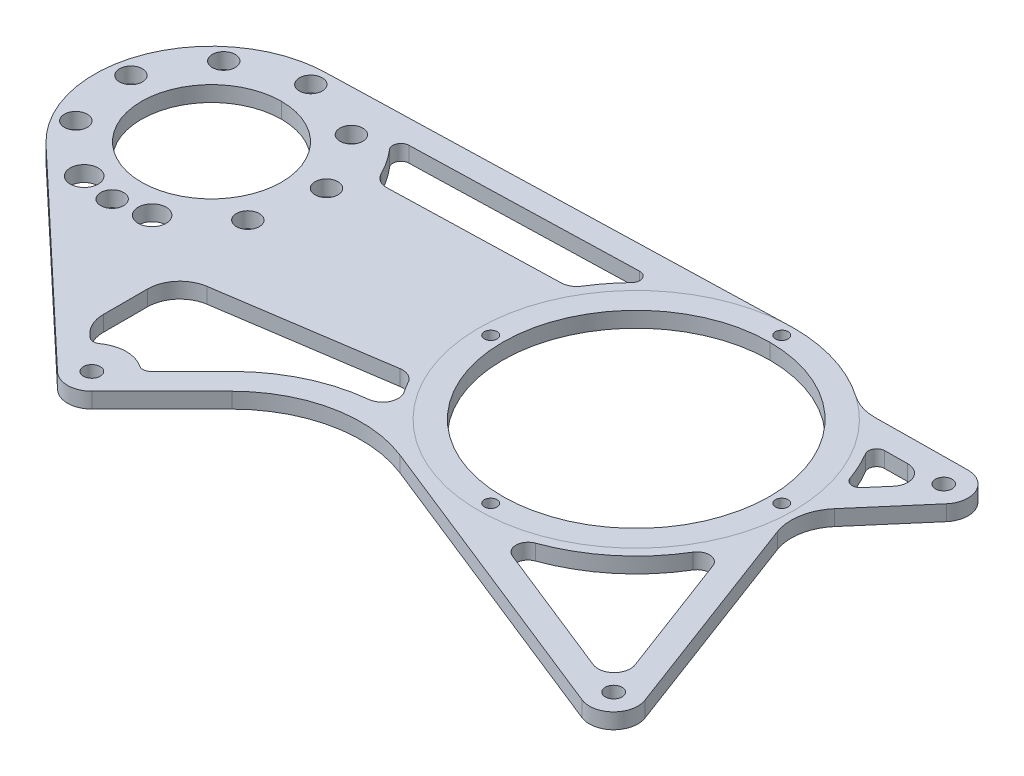
SolidWorks part; units mm, degrees
material "6061-T6 (SS)"
ref_plane "X-Y Datum" through (0, 0, 0) normal (0, 0, 1) x (1, 0, 0)
ref_plane "X-Z Datum" through (0, 0, 0) normal (0, 1, 0) x (1, 0, 0)
ref_plane "Y-Z Datum" through (0, 0, 0) normal (1, 0, 0) x (0, 0, -1)
sketch "Master Sketch " plane through (0, 0, 0) normal (0, 1, 0) x (1, 0, 0)
  line L0 (0, 0) -> (116.84, 0) construction
  line L1 (0, 0) -> (-54.61, 0) construction
  line L2 (116.84, 0) -> (228.6, 0) construction
  line L3 (228.6, 0) -> (228.6, 165.1) construction
  line L4 (123.19, 0) -> (123.19, 116.0018) construction
  line L5 (-54.61, 0) -> (-414.02, 0) construction
  line L6 (-54.61, 0) -> (-54.61, 127) construction
  line L7 (123.19, 168.4528) -> (123.19, 177.9778) construction
  line L8 (123.19, 116.0018) -> (228.6, 165.1) construction
  line L9 (123.19, 116.0018) -> (228.6, 0) construction
  line L10 (0, 0) -> (123.19, 116.0018) construction
  line L11 (0, 0) -> (-54.61, 127) construction
  line L12 (-54.61, 127) -> (123.19, 116.0018) construction
  line L13 (-54.61, 127) -> (228.6, 165.1) construction
  line L14 (0, 0) -> (0, 123.622) construction
  line L15 (-86.1521, 93.553) -> (-6.535, 18.4704)
  line L16 (-54.61, 172.974) -> (123.19, 177.9778)
  line L17 (192.5164, 124.5578) -> (212.8001, 148.1685)
  line L18 (169.599, 163.5141) -> (205.4727, 163.8999)
  line L19 (189.1339, 105.4429) -> (220.4344, 22.1488)
  line L20 (6.7352, 18.6648) -> (34.256, 46.1856)
  line L21 (207.987, 9.9519) -> (89.0101, 57.4446)
  circle A0 centre (0, 0) radius 12.7 construction
  circle A1 centre (228.6, 165.1) radius 12.7 construction
  circle A2 centre (228.6, 0) radius 12.7 construction
  circle A3 centre (-414.02, 0) radius 12.7 construction
  circle A4 centre (123.19, 116.0018) radius 52.451
  circle A5 centre (123.19, 116.0018) radius 57.15 construction
  circle A6 centre (123.19, 116.0018) radius 61.976 construction
  circle A7 centre (-54.61, 127) radius 45.974
  circle A8 centre (-54.61, 127) radius 39 construction
  circle A9 centre (205.5752, 154.3754) radius 3 construction
  circle A10 centre (211.5182, 18.7982) radius 3 construction
  circle A11 centre (0, 25.4) radius 3 construction
  circle A12 centre (0, 25.4) radius 9.525
  circle A13 centre (211.5182, 18.7982) radius 9.525
  circle A14 centre (205.5752, 154.3754) radius 9.525
  circle A15 centre (-67.9488, 90.352) radius 5.5
  circle A16 centre (-41.2712, 90.352) radius 5.5
  arc A17 (56.2619, 120.1418) -> (168.2859, 66.3745) centre (123.19, 116.0018) ccw construction
  arc A18 (123.19, 177.9778) -> (158.5311, 166.9138) centre (123.19, 116.0018) cw
  circle A19 centre (123.19, 116.0018) radius 67.056 construction
  arc A20 (192.5164, 124.5578) -> (189.1339, 105.4429) centre (206.9663, 112.1441) ccw
  arc A21 (169.599, 163.5141) -> (158.5311, 166.9138) centre (169.3942, 182.563) cw
  arc A22 (89.0101, 57.4446) -> (34.256, 46.1856) centre (70.177, 10.2646) ccw
  circle A23 centre (-54.61, 127) radius 25.908 construction
  circle A24 centre (-54.61, 127) radius 27.4955
  point P9 (123.19, 0)
  point P23 (-54.61, 166)
  point P27 (-41.2712, 163.648)
  point P28 (-29.5413, 156.8757)
  point P29 (-20.835, 146.5)
  point P30 (-16.2025, 133.7723)
  point P31 (-16.2025, 120.2277)
  point P32 (-20.835, 107.5)
  point P33 (-29.5413, 97.1243)
  point P34 (-41.2712, 90.352)
  point P35 (-54.61, 88)
  point P36 (-67.9488, 90.352)
  point P37 (-79.6787, 97.1243)
  point P38 (-88.385, 107.5)
  point P39 (-93.0175, 120.2277)
  point P40 (-93.0175, 133.7723)
  point P41 (-88.385, 146.5)
  point P42 (-79.6787, 156.8757)
  point P43 (-67.9488, 163.648)
  point P44 (-54.61, 127)
  point P66 (190.246, 116.0018)
  point P74 (185.166, 116.0018)
  point P77 (163.0683, 163.4438)
  point P80 (74.3713, 70.0317)
  point P85 (123.19, 173.1468)
  dimension "D1" = 105.41
  dimension "D2" = 25.4
  dimension "D8" = 116.0018
  dimension "D11" = 104.902
  dimension "D12" = 114.3
  dimension "D13" = 123.952
  dimension "D14" = 91.948
  dimension "D15" = 78
  dimension "D17" = 6
  dimension "D21" = 19.05
  dimension "D23" = 11
  dimension "D25" = 19.05
  dimension "D26" = 19.05
  dimension "D27" = 50.8
  dimension "D28" = 1.5875
  dimension "D30" = 51.816
  dimension "D3" = 165.1
  dimension "D4" = 171.45
  dimension "D5" = 111.76
  dimension "D6" = 116.84
  dimension "D7" = 54.61
  dimension "D9" = 642.62
  dimension "D10" = 127
  dimension "D18" = 25.4
  dimension "D19" = 25.4
  dimension "D20" = 25.4
  dimension "D22" = 228.6
  dimension "D29" = 45
  dimension "D24" = 5.08
  dimension "D16" = 18
extrude "Boss-Extrude2" add sketch "Master Sketch " along normal blind 6.096
hole_wizard "Ø5.0mm Dowel Hole1" positions "Sketch26" profile "Sketch27" hole size "Ø5.0" standard "ANSI Metric" end condition through all
sketch "Sketch26" plane through (0, 6.096, 0) normal (0, 1, 0) x (1, 0, 0)
  point P0 (123.19, 173.1468)
sketch "Sketch27" plane through (123.19, 6.096, -173.1468) normal (1, 0, 0) x (0, 0, 1)
  line L0 (0, 0) -> (0, 6.096)
  line L1 (0, 6.096) -> (2.5, 6.096)
  line L2 (2.5, 6.096) -> (2.5, 0)
  line L5 (2.5, 0) -> (0, 0)
  line L11 (0, -6.35) -> (0, 107.95) construction
  dimension "Thru Hole Dia." = 5
  dimension "Thru Hole Depth" = 6.096
pattern_circular "CirPattern4" count 4 over 360 about axis through (123.19, 0, -116.0018) along (0, 1, 0) of "Ø5.0mm Dowel Hole1"
hole_wizard "M6 Clearance Hole4" positions "Sketch20" profile "Sketch21" hole size "M6" standard "ANSI Metric" end condition through all
sketch "Sketch20" plane through (0, 6.096, 0) normal (0, 1, 0) x (1, 0, 0)
  point P0 (205.5752, 154.3754)
  point P3 (211.5182, 18.7982)
  point P6 (0, 25.4)
  point P9 (205.5752, 154.3754)
sketch "Sketch21" plane through (205.5752, 6.096, -154.3754) normal (1, 0, 0) x (0, 0, 1)
  line L0 (0, 0) -> (0, 6.096)
  line L1 (0, 6.096) -> (3.3, 6.096)
  line L2 (3.3, 6.096) -> (3.3, 0)
  line L5 (3.3, 0) -> (0, 0)
  line L11 (0, -6.35) -> (0, 107.95) construction
  dimension "Thru Hole Dia." = 6.6
  dimension "Thru Hole Depth" = 6.096
hole_wizard "M8 Clearance Hole1" positions "Sketch24" profile "Sketch25" hole size "M8" standard "ANSI Metric" end condition through all
sketch "Sketch24" plane through (0, 6.096, 0) normal (0, 1, 0) x (1, 0, 0)
  point P2 (-54.61, 166)
sketch "Sketch25" plane through (-54.61, 6.096, -166) normal (1, 0, 0) x (0, 0, 1)
  line L0 (0, 0) -> (0, 6.096)
  line L1 (0, 6.096) -> (4.5, 6.096)
  line L2 (4.5, 6.096) -> (4.5, 0)
  line L5 (4.5, 0) -> (0, 0)
  line L11 (0, -6.35) -> (0, 107.95) construction
  dimension "Thru Hole Dia." = 9
  dimension "Thru Hole Depth" = 6.096
pattern_circular "CirPattern3" count 18 over 360 about axis through (-54.61, 6.096, -127) along (0, -1, 0) skipping 1, 3, 5, 7, 8, 10, 11, 13, 15, 17 of "M8 Clearance Hole1"
ref_plane "Plane2" through (-54.61, 0, 0) normal (1, 0, 0) x (0, 0, -1)
ref_plane "Plane1" through (123.19, 0, 0) normal (1, 0, 0) x (0, 0, -1)
split line "Split Line2"
split line "Split Line3"
ref_point "Point2"
ref_point "Point3"
sketch "Sketch28" plane through (0, 6.096, 0) normal (0, 1, 0) x (1, 0, 0)
  circle A0 centre (123.19, 116.0018) radius 61.976 construction
  circle A1 centre (123.19, 116.0018) radius 61.976
split line "Split Line4"
sketch "Topology 1" plane through (0, 6.096, 0) normal (0, 1, 0) x (1, 0, 0)
  line L0 (145.3498, 45.211) -> (198.1607, 24.1302)
  line L1 (206.4589, 32.2614) -> (188.0555, 81.2349)
  line L2 (191.5509, 154.2246) -> (182.6033, 154.1284)
  line L3 (92.5413, 66.2908) -> (211.5182, 18.7982) construction
  line L4 (211.5182, 18.7982) -> (180.2176, 102.0923) construction
  line L5 (190.6048, 136.9496) -> (196.4358, 143.737)
  line L6 (185.2915, 130.7647) -> (205.5752, 154.3754) construction
  line L7 (205.5752, 154.3754) -> (169.7015, 153.9896) construction
  line L8 (6.7352, 18.6648) -> (34.256, 46.1856) construction
  line L9 (119.7044, 177.8797) -> (123.19, 177.9778) construction
  line L10 (119.7044, 177.8797) -> (123.19, 177.9778)
  line L11 (6.7352, 18.6648) -> (34.256, 46.1856)
  line L12 (11.5992, 36.9992) -> (27.5208, 52.9208)
  line L14 (-17.1171, 47.0221) -> (-17.1171, 64.3926)
  line L15 (-6.3073, 76.9512) -> (59.5874, 86.8686)
  line L16 (119.7044, 177.8797) -> (-54.61, 172.974)
  line L17 (-86.1521, 93.553) -> (-6.535, 18.4704)
  line L18 (6.7352, 18.6648) -> (34.256, 46.1856)
  line L19 (89.0101, 57.4446) -> (207.987, 9.9519)
  line L20 (220.4344, 22.1488) -> (189.1339, 105.4429)
  line L21 (192.5164, 124.5578) -> (212.8001, 148.1685)
  line L22 (205.4727, 163.8999) -> (169.599, 163.5141)
  line L23 (119.7044, 177.8797) -> (-54.61, 172.974)
  line L24 (-86.1521, 93.553) -> (-6.535, 18.4704)
  line L26 (89.0101, 57.4446) -> (207.987, 9.9519)
  line L27 (220.4344, 22.1488) -> (189.1339, 105.4429)
  line L28 (192.5164, 124.5578) -> (212.8001, 148.1685)
  line L29 (205.4727, 163.8999) -> (169.599, 163.5141)
  line L30 (73.4651, 167.0496) -> (-14.7002, 164.5684)
  line L31 (-4.4748, 145.7986) -> (62.0635, 147.6712)
  line L32 (-13.1304, 37.7826) -> (-11.934, 36.6543)
  line L33 (119.9724, 168.3585) -> (-54.342, 163.4528) construction
  line L34 (0, 25.4) -> (27.5208, 52.9208) construction
  arc A0 (158.5311, 166.9138) -> (123.19, 177.9778) centre (123.19, 116.0018) ccw construction
  arc A1 (158.5311, 166.9138) -> (123.19, 177.9778) centre (123.19, 116.0018) ccw
  arc A2 (145.5002, 54.1144) -> (179.5195, 82.0197) centre (123.19, 116.0018) ccw
  arc A3 (179.5195, 82.0197) -> (188.0555, 81.2349) centre (183.5974, 79.5596) cw
  arc A4 (119.4901, 181.6837) -> (160.7037, 170.0436) centre (123.19, 116.0018) ccw construction
  arc A5 (145.5002, 54.1144) -> (145.3498, 45.211) centre (147.1154, 49.6341) ccw
  arc A6 (206.4589, 32.2614) -> (198.1607, 24.1302) centre (200.5148, 30.0277) cw
  arc A7 (172.1385, 154.0158) -> (183.7852, 129.0114) centre (123.19, 116.0018) cw
  arc A8 (158.5311, 166.9138) -> (169.599, 163.5141) centre (169.3942, 182.563) ccw
  arc A9 (119.7044, 177.8797) -> (158.5311, 166.9138) centre (123.19, 116.0018) ccw
  arc A10 (-54.61, 172.974) -> (-86.1521, 93.553) centre (-54.61, 127) ccw
  arc A11 (-6.535, 18.4704) -> (6.7352, 18.6648) centre (0, 25.4) ccw
  arc A12 (89.0101, 57.4446) -> (34.256, 46.1856) centre (70.177, 10.2646) ccw
  arc A13 (207.987, 9.9519) -> (220.4344, 22.1488) centre (211.5182, 18.7982) ccw
  arc A14 (192.5164, 124.5578) -> (189.1339, 105.4429) centre (206.9663, 112.1441) ccw
  arc A15 (212.8001, 148.1685) -> (205.4727, 163.8999) centre (205.5752, 154.3754) ccw
  arc A16 (158.5311, 166.9138) -> (169.599, 163.5141) centre (169.3942, 182.563) ccw
  arc A17 (119.7044, 177.8797) -> (158.5311, 166.9138) centre (123.19, 116.0018) ccw
  arc A18 (-54.61, 172.974) -> (-86.1521, 93.553) centre (-54.61, 127) ccw
  arc A19 (-6.535, 18.4704) -> (6.7352, 18.6648) centre (0, 25.4) ccw
  arc A21 (207.987, 9.9519) -> (220.4344, 22.1488) centre (211.5182, 18.7982) ccw
  arc A22 (192.5164, 124.5578) -> (189.1339, 105.4429) centre (206.9663, 112.1441) ccw
  arc A23 (212.8001, 148.1685) -> (205.4727, 163.8999) centre (205.5752, 154.3754) ccw
  arc A24 (179.9004, 149.3443) -> (185.2036, 137.9589) centre (123.19, 116.0018) cw
  arc A25 (175.1477, 156.3527) -> (187.5103, 129.8112) centre (123.19, 116.0018) cw construction
  arc A26 (190.6048, 136.9496) -> (185.2036, 137.9589) centre (188.1965, 139.0186) cw
  arc A27 (182.6033, 154.1284) -> (179.9004, 149.3443) centre (182.6374, 150.9535) ccw
  arc A28 (196.4358, 143.737) -> (191.5509, 154.2246) centre (191.6192, 147.875) ccw
  arc A29 (89.0101, 57.4446) -> (34.256, 46.1856) centre (70.177, 10.2646) ccw construction
  arc A30 (89.0101, 57.4446) -> (34.256, 46.1856) centre (70.177, 10.2646) ccw
  arc A31 (63.8869, 70.2607) -> (27.5208, 52.9208) centre (70.177, 10.2646) ccw
  arc A32 (7.5766, 36.6135) -> (-7.9019, 36.3867) centre (0, 25.4) ccw
  arc A33 (67.8443, 88.1113) -> (82.4046, 69.3373) centre (123.19, 116.0018) ccw
  arc A34 (65.8116, 83.8223) -> (68.3344, 79.6884) centre (123.19, 116.0018) ccw
  arc A35 (64.4419, 86.3967) -> (79.8973, 66.4686) centre (123.19, 116.0018) ccw construction
  arc A36 (-10.3254, 149.2911) -> (-17.0182, 159.3246) centre (-54.61, 127) ccw
  arc A37 (70.0507, 147.896) -> (88.6754, 167.4777) centre (123.19, 116.0018) cw
  arc A38 (67.2815, 150.6721) -> (75.8397, 161.6717) centre (123.19, 116.0018) cw
  arc A39 (66.7839, 149.8567) -> (86.5536, 170.6422) centre (123.19, 116.0018) cw construction
  arc A40 (-17.0182, 159.3246) -> (-14.7002, 164.5684) centre (-14.6109, 161.3947) cw
  arc A41 (92.5413, 66.2908) -> (27.5208, 52.9208) centre (70.177, 10.2646) ccw construction
  arc A42 (-10.3254, 149.2911) -> (-4.4748, 145.7986) centre (-4.6534, 152.1461) ccw
  arc A43 (67.2815, 150.6721) -> (62.0635, 147.6712) centre (61.8849, 154.0187) cw
  arc A44 (75.8397, 161.6717) -> (73.4651, 167.0496) centre (73.5544, 163.8759) ccw
  arc A45 (-6.3073, 76.9512) -> (-17.1171, 64.3926) centre (-4.4171, 64.3926) ccw
  arc A46 (-17.1171, 47.0221) -> (-13.1304, 37.7826) centre (-4.4171, 47.0221) ccw
  arc A47 (7.5766, 36.6135) -> (11.5992, 36.9992) centre (9.3541, 39.2442) ccw
  arc A48 (-7.9019, 36.3867) -> (-11.934, 36.6543) centre (-9.7557, 38.9642) cw
  arc A49 (65.8116, 83.8223) -> (59.5874, 86.8686) centre (60.4947, 80.8405) ccw
  arc A50 (68.3344, 79.6884) -> (63.8869, 70.2607) centre (63.2512, 76.3235) cw
  point P69 (-79.6171, 100.4826)
  point P105 (-17.1171, 75.3242)
  point P108 (-17.1171, 41.5422)
  dimension "D4" = 4.7625
  dimension "D5" = 6.35
  dimension "D8" = 3.175
  dimension "D9" = 6.35
  dimension "D11" = 3.175
  dimension "D17" = 6.35
  dimension "D18" = 6.35
  dimension "D19" = 3.175
  dimension "D20" = 12.7
  dimension "D21" = 12.7
  dimension "D22" = 3.175
  dimension "D23" = 6.096
  dimension "D14" = 19.05
  dimension "D15" = 33.782
  dimension "D1" = 0
  dimension "D2" = 9.525
  dimension "D3" = 3.81
  dimension "D6" = 9.525
  dimension "D7" = 3.81
  dimension "D10" = 9.525
  dimension "D12" = 3.81
  dimension "D13" = 9.525
  dimension "D16" = 3.81
sketch "Topology 3" plane through (0, 6.096, 0) normal (0, 1, 0) x (1, 0, 0)
  line L0 (148.2326, 44.0603) -> (198.1607, 24.1302)
  line L1 (206.4589, 32.2614) -> (188.9001, 78.9873)
  line L2 (191.5509, 154.2246) -> (181.8702, 154.1205)
  line L3 (190.1271, 136.3935) -> (196.4358, 143.737)
  line L4 (185.2915, 130.7647) -> (205.5752, 154.3754) construction
  line L5 (14.5483, 39.9483) -> (27.5208, 52.9208)
  line L6 (-33.0323, 56.5509) -> (-14.9683, 39.5158)
  line L7 (119.7044, 177.8797) -> (-54.61, 172.974)
  line L8 (-86.1521, 93.553) -> (-6.535, 18.4704)
  line L9 (6.7352, 18.6648) -> (34.256, 46.1856)
  line L10 (89.0101, 57.4446) -> (207.987, 9.9519)
  line L11 (220.4344, 22.1488) -> (189.1339, 105.4429)
  line L12 (192.5164, 124.5578) -> (212.8001, 148.1685)
  line L13 (205.4727, 163.8999) -> (169.599, 163.5141)
  line L14 (119.7044, 177.8797) -> (-54.61, 172.974)
  line L15 (-86.1521, 93.553) -> (-6.535, 18.4704)
  line L16 (6.7352, 18.6648) -> (34.256, 46.1856)
  line L17 (89.0101, 57.4446) -> (207.987, 9.9519)
  line L18 (220.4344, 22.1488) -> (189.1339, 105.4429)
  line L19 (192.5164, 124.5578) -> (212.8001, 148.1685)
  line L20 (205.4727, 163.8999) -> (169.599, 163.5141)
  line L21 (-8.2128, 94.6203) -> (-2.2782, 94.6203)
  line L22 (0.802, 94.9995) -> (48.4864, 106.9206)
  line L23 (60.6168, 166.688) -> (-2.3174, 164.9169)
  line L24 (7.0763, 124.3469) -> (55.6731, 136.4961)
  line L25 (-33.2992, 74.7707) -> (-16.7199, 91.3501)
  line L26 (119.9724, 168.3585) -> (-54.342, 163.4528) construction
  line L27 (-79.6171, 100.4826) -> (0, 25.4) construction
  line L28 (0, 25.4) -> (27.5208, 52.9208) construction
  line L29 (92.5413, 66.2908) -> (211.5182, 18.7982) construction
  line L30 (211.5182, 18.7982) -> (180.2176, 102.0923) construction
  line L32 (205.5752, 154.3754) -> (169.7015, 153.9896) construction
  arc A0 (123.19, 54.0258) -> (182.1581, 96.9285) centre (123.19, 116.0018) ccw
  arc A1 (148.1536, 55.8231) -> (177.6482, 80.2392) centre (123.19, 116.0018) ccw
  arc A2 (172.1385, 154.0158) -> (183.7852, 129.0114) centre (123.19, 116.0018) cw
  arc A3 (179.1759, 149.3219) -> (184.7202, 137.4188) centre (123.19, 116.0018) cw
  arc A4 (59.8962, 69.7071) -> (27.5208, 52.9208) centre (70.177, 10.2646) ccw
  arc A5 (4.5307, 37.742) -> (-4.8904, 37.6039) centre (0, 25.4) ccw
  arc A7 (61.4889, 110.1712) -> (82.4046, 69.3373) centre (123.19, 116.0018) ccw
  arc A8 (158.5311, 166.9138) -> (169.599, 163.5141) centre (169.3942, 182.563) ccw
  arc A9 (119.7044, 177.8797) -> (158.5311, 166.9138) centre (123.19, 116.0018) ccw
  arc A10 (-54.61, 172.974) -> (-86.1521, 93.553) centre (-54.61, 127) ccw
  arc A11 (-6.535, 18.4704) -> (6.7352, 18.6648) centre (0, 25.4) ccw
  arc A12 (89.0101, 57.4446) -> (34.256, 46.1856) centre (70.177, 10.2646) ccw
  arc A13 (207.987, 9.9519) -> (220.4344, 22.1488) centre (211.5182, 18.7982) ccw
  arc A14 (192.5164, 124.5578) -> (189.1339, 105.4429) centre (206.9663, 112.1441) ccw
  arc A15 (212.8001, 148.1685) -> (205.4727, 163.8999) centre (205.5752, 154.3754) ccw
  arc A16 (158.5311, 166.9138) -> (169.599, 163.5141) centre (169.3942, 182.563) ccw
  arc A17 (119.7044, 177.8797) -> (158.5311, 166.9138) centre (123.19, 116.0018) ccw
  arc A18 (-54.61, 172.974) -> (-86.1521, 93.553) centre (-54.61, 127) ccw
  arc A19 (-6.535, 18.4704) -> (6.7352, 18.6648) centre (0, 25.4) ccw
  arc A20 (89.0101, 57.4446) -> (34.256, 46.1856) centre (70.177, 10.2646) ccw
  arc A21 (207.987, 9.9519) -> (220.4344, 22.1488) centre (211.5182, 18.7982) ccw
  arc A22 (192.5164, 124.5578) -> (189.1339, 105.4429) centre (206.9663, 112.1441) ccw
  arc A23 (212.8001, 148.1685) -> (205.4727, 163.8999) centre (205.5752, 154.3754) ccw
  arc A24 (60.0304, 100.017) -> (66.5532, 83.8005) centre (123.19, 116.0018) ccw
  arc A25 (63.439, 132.459) -> (88.6754, 167.4777) centre (123.19, 116.0018) cw
  arc A26 (64.1096, 143.4637) -> (68.8318, 151.9162) centre (123.19, 116.0018) cw
  arc A27 (-4.7007, 132.5372) -> (-10.4297, 150.8683) centre (-54.61, 127) ccw
  arc A28 (92.5413, 66.2908) -> (27.5208, 52.9208) centre (70.177, 10.2646) ccw construction
  arc A29 (58.328, 109.8725) -> (80.3152, 66.9467) centre (123.19, 116.0018) ccw construction
  arc A30 (60.378, 133.3021) -> (86.9072, 170.1148) centre (123.19, 116.0018) cw construction
  arc A31 (123.19, 50.8508) -> (185.179, 95.9514) centre (123.19, 116.0018) ccw construction
  arc A32 (174.6461, 155.9633) -> (186.8894, 129.6779) centre (123.19, 116.0018) cw construction
  arc A33 (206.4589, 32.2614) -> (198.1607, 24.1302) centre (200.5148, 30.0277) cw
  arc A34 (188.9001, 78.9873) -> (177.6482, 80.2392) centre (182.956, 76.7536) ccw
  arc A35 (148.1536, 55.8231) -> (148.2326, 44.0603) centre (150.5867, 49.9578) ccw
  arc A36 (184.7202, 137.4188) -> (190.1271, 136.3935) centre (187.7188, 138.4625) ccw
  arc A37 (181.8702, 154.1205) -> (179.1759, 149.3219) centre (181.9043, 150.9457) ccw
  arc A38 (196.4358, 143.737) -> (191.5509, 154.2246) centre (191.6192, 147.875) ccw
  arc A39 (14.5483, 39.9483) -> (4.5307, 37.742) centre (7.8131, 46.6835) cw
  arc A40 (-4.8904, 37.6039) -> (-14.9683, 39.5158) centre (-8.4334, 46.4454) cw
  arc A42 (48.4864, 106.9206) -> (60.0304, 100.017) centre (50.7965, 97.68) cw
  arc A43 (59.8962, 69.7071) -> (66.5532, 83.8005) centre (58.2729, 79.0927) ccw
  arc A44 (-2.2782, 94.6203) -> (0.802, 94.9995) centre (-2.2782, 107.3203) ccw
  arc A45 (-16.7199, 91.3501) -> (-8.2128, 94.6203) centre (-8.2128, 81.9203) cw
  arc A46 (-2.3174, 164.9169) -> (-10.4297, 150.8683) centre (-2.0494, 155.3957) ccw
  arc A47 (7.0763, 124.3469) -> (-4.7007, 132.5372) centre (4.7662, 133.5875) cw
  arc A48 (55.6731, 136.4961) -> (64.1096, 143.4637) centre (52.5929, 148.8169) ccw
  arc A49 (68.8318, 151.9162) -> (60.6168, 166.688) centre (60.8847, 157.1668) ccw
  arc A50 (-33.2992, 74.7707) -> (-33.0323, 56.5509) centre (-24.319, 65.7905) ccw
  dimension "D11" = 6.35
  dimension "D12" = 6.35
  dimension "D13" = 3.175
  dimension "D14" = 6.35
  dimension "D15" = 9.525
  dimension "D16" = 12.7
  dimension "D17" = 9.525
  dimension "D18" = 12.7
  dimension "D19" = 12.7
  dimension "D21" = 9.525
  dimension "D22" = 9.525
  dimension "D23" = 12.7
  dimension "D24" = 9.525
  dimension "D1" = 0
  dimension "D2" = 9.525
  dimension "D3" = 3.175
  dimension "D4" = 9.525
  dimension "D5" = 3.175
  dimension "D6" = 9.525
  dimension "D7" = 9.525
  dimension "D8" = 3.175
  dimension "D9" = 9.525
  dimension "D10" = 3.175
sketch "Topology (50%)" plane through (0, 6.096, 0) normal (0, 1, 0) x (1, 0, 0)
  line L0 (-37.2037, 60.4796) -> (-14.9683, 39.5158)
  line L2 (191.5509, 154.2246) -> (181.8702, 154.1205)
  line L3 (190.1271, 136.3935) -> (196.4358, 143.737)
  line L4 (191.5509, 154.2246) -> (181.8702, 154.1205)
  line L5 (190.1271, 136.3935) -> (196.4358, 143.737)
  line L6 (148.2326, 44.0603) -> (198.1607, 24.1302)
  line L7 (192.5164, 124.5578) -> (212.8001, 148.1685)
  line L8 (220.4344, 22.1488) -> (189.1339, 105.4429)
  line L9 (89.0101, 57.4446) -> (207.987, 9.9519)
  line L10 (6.7352, 18.6648) -> (34.256, 46.1856)
  line L11 (-86.1521, 93.553) -> (-6.535, 18.4704)
  line L12 (119.7044, 177.8797) -> (-54.61, 172.974)
  line L13 (205.4727, 163.8999) -> (169.599, 163.5141)
  line L14 (192.5164, 124.5578) -> (212.8001, 148.1685)
  line L15 (220.4344, 22.1488) -> (189.1339, 105.4429)
  line L16 (89.0101, 57.4446) -> (207.987, 9.9519)
  line L17 (6.7352, 18.6648) -> (34.256, 46.1856)
  line L18 (-86.1521, 93.553) -> (-6.535, 18.4704)
  line L19 (119.7044, 177.8797) -> (-54.61, 172.974)
  line L20 (205.4727, 163.8999) -> (169.599, 163.5141)
  line L21 (206.4589, 32.2614) -> (188.9001, 78.9873)
  line L22 (148.2326, 44.0603) -> (198.1607, 24.1302)
  line L23 (206.4589, 32.2614) -> (188.9001, 78.9873)
  line L24 (60.6168, 166.688) -> (-2.3174, 164.9169)
  line L25 (7.0763, 124.3469) -> (55.6731, 136.4961)
  line L26 (60.6168, 166.688) -> (-2.3174, 164.9169)
  line L27 (-33.0323, 56.5509) -> (-14.9683, 39.5158)
  line L28 (14.5483, 39.9483) -> (27.5208, 52.9208)
  line L29 (48.4864, 106.9206) -> (0.802, 94.9995)
  line L30 (-2.2782, 94.6203) -> (-8.2128, 94.6203)
  line L31 (-17.6426, 90.4274) -> (-33.2992, 74.7707)
  line L33 (14.5483, 39.9483) -> (27.5208, 52.9208)
  arc A0 (123.19, 54.0258) -> (182.1581, 96.9285) centre (123.19, 116.0018) ccw construction
  arc A1 (183.7852, 129.0114) -> (172.1385, 154.0158) centre (123.19, 116.0018) ccw construction
  arc A2 (61.4889, 110.1712) -> (82.4046, 69.3373) centre (123.19, 116.0018) ccw construction
  arc A3 (88.6754, 167.4777) -> (63.439, 132.459) centre (123.19, 116.0018) ccw construction
  arc A4 (181.8702, 154.1205) -> (179.1759, 149.3219) centre (181.9043, 150.9457) ccw
  arc A5 (184.7202, 137.4188) -> (179.1759, 149.3219) centre (123.19, 116.0018) ccw
  arc A6 (184.7202, 137.4188) -> (190.1271, 136.3935) centre (187.7188, 138.4625) ccw
  arc A7 (196.4358, 143.737) -> (191.5509, 154.2246) centre (191.6192, 147.875) ccw
  arc A8 (192.5164, 124.5578) -> (189.1339, 105.4429) centre (206.9663, 112.1441) ccw
  arc A9 (207.987, 9.9519) -> (220.4344, 22.1488) centre (211.5182, 18.7982) ccw
  arc A10 (89.0101, 57.4446) -> (34.256, 46.1856) centre (70.177, 10.2646) ccw
  arc A11 (-6.535, 18.4704) -> (6.7352, 18.6648) centre (0, 25.4) ccw
  arc A12 (-54.61, 172.974) -> (-86.1521, 93.553) centre (-54.61, 127) ccw
  arc A13 (119.7044, 177.8797) -> (158.5311, 166.9138) centre (123.19, 116.0018) ccw
  arc A14 (158.5311, 166.9138) -> (169.599, 163.5141) centre (169.3942, 182.563) ccw
  arc A15 (212.8001, 148.1685) -> (205.4727, 163.8999) centre (205.5752, 154.3754) ccw
  arc A16 (192.5164, 124.5578) -> (189.1339, 105.4429) centre (206.9663, 112.1441) ccw
  arc A17 (207.987, 9.9519) -> (220.4344, 22.1488) centre (211.5182, 18.7982) ccw
  arc A18 (89.0101, 57.4446) -> (34.256, 46.1856) centre (70.177, 10.2646) ccw
  arc A19 (-6.535, 18.4704) -> (6.7352, 18.6648) centre (0, 25.4) ccw
  arc A20 (-54.61, 172.974) -> (-86.1521, 93.553) centre (-54.61, 127) ccw
  arc A21 (119.7044, 177.8797) -> (158.5311, 166.9138) centre (123.19, 116.0018) ccw
  arc A22 (158.5311, 166.9138) -> (169.599, 163.5141) centre (169.3942, 182.563) ccw
  arc A23 (212.8001, 148.1685) -> (205.4727, 163.8999) centre (205.5752, 154.3754) ccw
  arc A24 (181.8702, 154.1205) -> (179.1759, 149.3219) centre (181.9043, 150.9457) ccw
  arc A25 (184.7202, 137.4188) -> (179.1759, 149.3219) centre (123.19, 116.0018) ccw
  arc A26 (184.7202, 137.4188) -> (190.1271, 136.3935) centre (187.7188, 138.4625) ccw
  arc A27 (196.4358, 143.737) -> (191.5509, 154.2246) centre (191.6192, 147.875) ccw
  arc A28 (198.1607, 24.1302) -> (206.4589, 32.2614) centre (200.5148, 30.0277) ccw
  arc A29 (188.9001, 78.9873) -> (177.6482, 80.2392) centre (182.956, 76.7536) ccw
  arc A30 (148.1536, 55.8231) -> (177.6482, 80.2392) centre (123.19, 116.0018) ccw
  arc A31 (148.1536, 55.8231) -> (148.2326, 44.0603) centre (150.5867, 49.9578) ccw
  arc A32 (198.1607, 24.1302) -> (206.4589, 32.2614) centre (200.5148, 30.0277) ccw
  arc A33 (188.9001, 78.9873) -> (177.6482, 80.2392) centre (182.956, 76.7536) ccw
  arc A34 (148.1536, 55.8231) -> (177.6482, 80.2392) centre (123.19, 116.0018) ccw
  arc A35 (148.1536, 55.8231) -> (148.2326, 44.0603) centre (150.5867, 49.9578) ccw
  arc A36 (123.19, 54.0258) -> (182.1581, 96.9285) centre (123.19, 116.0018) ccw
  arc A37 (183.7852, 129.0114) -> (172.1385, 154.0158) centre (123.19, 116.0018) ccw
  arc A38 (-2.3174, 164.9169) -> (-10.4297, 150.8683) centre (-2.0494, 155.3957) ccw
  arc A39 (-4.7007, 132.5372) -> (-10.4297, 150.8683) centre (-54.61, 127) ccw
  arc A40 (-4.7007, 132.5372) -> (7.0763, 124.3469) centre (4.7662, 133.5875) ccw
  arc A41 (55.6731, 136.4961) -> (64.1096, 143.4637) centre (52.5929, 148.8169) ccw
  arc A42 (-14.9683, 39.5158) -> (-4.8904, 37.6039) centre (-8.4334, 46.4454) ccw
  arc A43 (4.5307, 37.742) -> (-4.8904, 37.6039) centre (0, 25.4) ccw
  arc A44 (4.5307, 37.742) -> (14.5483, 39.9483) centre (7.8131, 46.6835) ccw
  arc A45 (59.8962, 69.7071) -> (27.5208, 52.9208) centre (70.177, 10.2646) ccw
  arc A46 (59.8962, 69.7071) -> (66.5532, 83.8005) centre (58.2729, 79.0927) ccw
  arc A47 (60.0304, 100.017) -> (66.5532, 83.8005) centre (123.19, 116.0018) ccw
  arc A48 (60.0304, 100.017) -> (48.4864, 106.9206) centre (50.7965, 97.68) ccw
  arc A49 (-2.2782, 94.6203) -> (0.802, 94.9995) centre (-2.2782, 107.3203) ccw
  arc A50 (-8.2128, 94.6203) -> (-17.6426, 90.4274) centre (-8.2128, 81.9203) ccw
  arc A52 (-14.9683, 39.5158) -> (-4.8904, 37.6039) centre (-8.4334, 46.4454) ccw
  arc A53 (4.5307, 37.742) -> (-4.8904, 37.6039) centre (0, 25.4) ccw
  arc A54 (4.5307, 37.742) -> (14.5483, 39.9483) centre (7.8131, 46.6835) ccw
  arc A55 (59.8962, 69.7071) -> (27.5208, 52.9208) centre (70.177, 10.2646) ccw
  arc A56 (59.8962, 69.7071) -> (66.5532, 83.8005) centre (58.2729, 79.0927) ccw
  arc A57 (60.0304, 100.017) -> (66.5532, 83.8005) centre (123.19, 116.0018) ccw
  arc A62 (68.8318, 151.9162) -> (64.1096, 143.4637) centre (123.19, 116.0018) ccw
  arc A63 (68.8318, 151.9162) -> (60.6168, 166.688) centre (60.8847, 157.1668) ccw
  arc A64 (-2.3174, 164.9169) -> (-10.4297, 150.8683) centre (-2.0494, 155.3957) ccw
  arc A65 (-4.7007, 132.5372) -> (-10.4297, 150.8683) centre (-54.61, 127) ccw
  arc A69 (68.8318, 151.9162) -> (60.6168, 166.688) centre (60.8847, 157.1668) ccw
  arc A70 (61.4889, 110.1712) -> (82.4046, 69.3373) centre (123.19, 116.0018) ccw
  arc A71 (88.6754, 167.4777) -> (63.439, 132.459) centre (123.19, 116.0018) ccw
  arc A72 (-33.7876, 81.3051) -> (-10.4297, 150.8683) centre (-54.61, 127) ccw
  arc A73 (148.1536, 55.8231) -> (177.6482, 80.2392) centre (123.19, 116.0018) ccw
  arc A74 (68.8318, 151.9162) -> (66.5532, 83.8005) centre (123.19, 116.0018) ccw
  arc A75 (184.7202, 137.4188) -> (179.1759, 149.3219) centre (123.19, 116.0018) ccw
  arc A76 (188.0521, 109.8735) -> (188.3408, 116.1433) centre (123.19, 116.0018) ccw
  arc A77 (-37.2037, 60.4796) -> (-33.7876, 81.3051) centre (-28.5215, 69.7484) cw
  arc A88 (-33.2992, 74.7707) -> (-33.0323, 56.5509) centre (-24.319, 65.7905) ccw
  point P99 (-54.61, 76.7845)
  dimension "D6" = 12.7
  dimension "D7" = 24.8294
  dimension "D8" = 30.5597
  dimension "D1" = 0
  dimension "D2" = 0
  dimension "D3" = 0
  dimension "D4" = 0
  dimension "D5" = 0
extrude "Cut-Extrude1" cut sketch "Topology 1" against normal through all contours A38 A44 L30 A40 A36 A42 L31 A43 | A50 A34 A49 L15 A45 L14 A46 L32 A48 A32 A47 L12 A31 | A6 L1 A3 A2 A5 L0 | L5 A28 L2 A27 A24 A26
extrude "Cut-Extrude2" [suppressed] cut sketch "Topology 3" against normal through all
extrude "Cut-Extrude3" [suppressed] cut sketch "Topology (50%)" against normal through all contours A77 L0 A52 A53 A54 L33 A55 A56 A57 A74 A69 L26 A64 A65 A72 | A34 A35 L22 A32 L23 A33 | L5 A27 L4 A24 A25 A26
